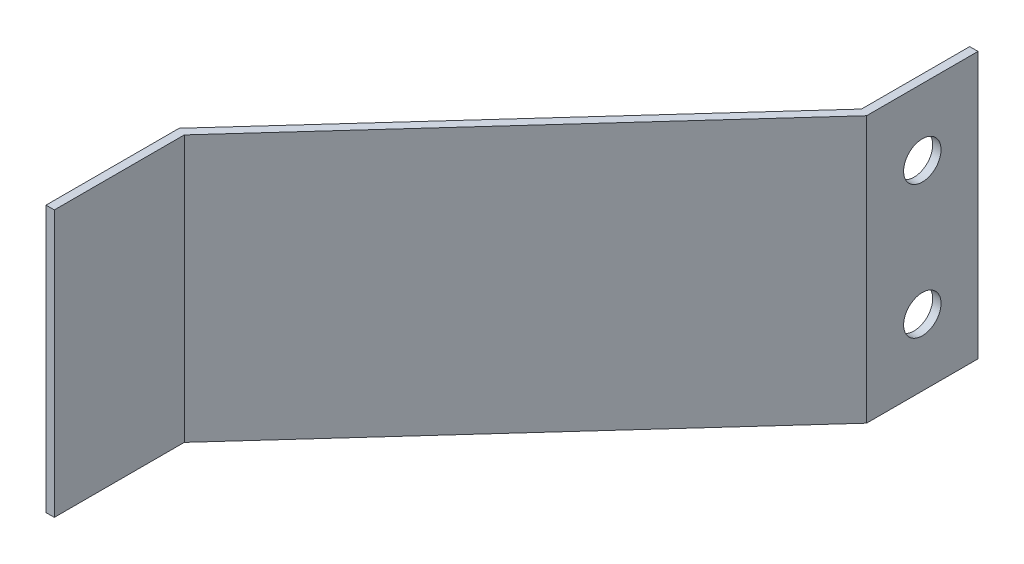
SolidWorks part; units mm, degrees
material "AISI 1020 Steel, Cold Rolled"
ref_plane "Front Plane" through (0, 0, 0) normal (0, 0, 1) x (1, 0, 0)
ref_plane "Top Plane" through (0, 0, 0) normal (0, 1, 0) x (1, 0, 0)
ref_plane "Right Plane" through (0, 0, 0) normal (1, 0, 0) x (0, 0, -1)
sketch "Sketch1" plane through (0, 0, 0) normal (0, 1, 0) x (1, 0, 0)
  line L1 (-88.9, 99.06) -> (38.1, 99.06)
  line L2 (-88.9, 99.06) -> (-88.9, -129.54)
  line L3 (-88.9, -129.54) -> (38.1, -129.54)
  line L4 (38.1, 99.06) -> (38.1, -129.54)
  dimension "D1" = 228.6
  dimension "D2" = 129.54
  dimension "D3" = 127
  dimension "D4" = 88.9
extrude "Boss-Extrude1" add sketch "Sketch1" along normal blind 101.6
sketch "Sketch3" plane through (0, 101.6, 0) normal (0, 1, 0) x (1, 0, 0)
  line L0 (34.925, 99.06) -> (34.925, 57.785)
  line L1 (38.1, 99.06) -> (-88.9, 99.06) construction
  line L2 (34.925, 57.785) -> (-88.9, -78.74)
  line L3 (-88.9, 99.06) -> (-88.9, -129.54) construction
  line L4 (-88.9, -129.54) -> (38.1, -129.54) construction
  line L5 (-88.9, -78.74) -> (-88.9, -129.54)
  line L6 (-88.9, -129.54) -> (-85.725, -129.54)
  line L7 (-85.725, -129.54) -> (-85.725, -79.9654)
  line L8 (-85.725, -79.9654) -> (38.1, 56.5596)
  line L9 (38.1, -129.54) -> (38.1, 99.06) construction
  line L10 (-88.9, -78.74) -> (-88.9, 99.06)
  line L11 (-88.9, 99.06) -> (34.925, 99.06)
  line L12 (-85.725, -129.54) -> (38.1, -129.54)
  line L13 (38.1, -129.54) -> (38.1, 56.5596)
  line M1 (-88.9, 99.06) -> (-88.9, -129.54)
  line M2 (-88.9, -129.54) -> (38.1, -129.54)
  line M3 (38.1, -129.54) -> (38.1, 99.06)
  line M4 (38.1, 99.06) -> (-88.9, 99.06)
  dimension "D1" = 41.275
  dimension "D2" = 50.8
  dimension "D3" = 3.175
  dimension "D4" = 3.175
  dimension "D5" = 3.175
extrude "Cut-Extrude3" cut sketch "Sketch3" against normal through all contours L2 L0 M4 M1 | L8 L7 M2 M3
sketch "Sketch6" plane through (38.1, 0, 0) normal (1, 0, 0) x (0, 0, -1)
  line L1 (77.8098, 101.6) -> (77.8098, 0) construction
  line L2 (56.5596, 101.6) -> (99.06, 101.6) construction
  line L3 (56.5596, 0) -> (99.06, 0) construction
  circle A0 centre (77.8098, 76.2) radius 7.1438
  circle A1 centre (77.8098, 25.4) radius 7.1438
  dimension "D1" = 14.2875
  dimension "D2" = 14.2875
  dimension "D3" = 0
  dimension "D4" = 0
  dimension "D5" = 25.4
  dimension "D6" = 25.4
extrude "Cut-Extrude4" cut sketch "Sketch6" against normal blind 101.6
